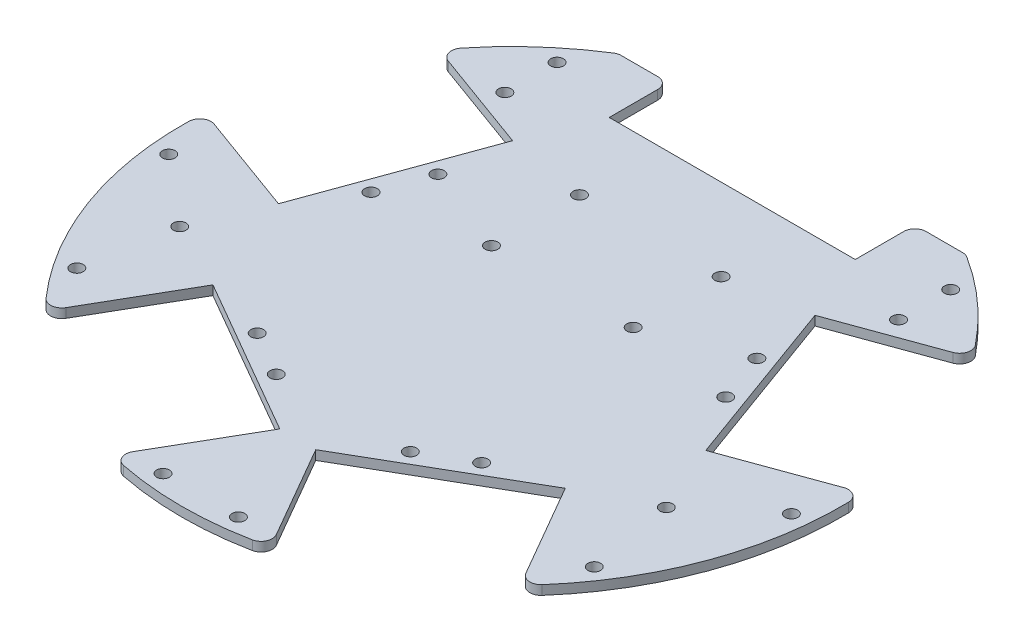
SolidWorks part; units mm, degrees
ref_plane "Front Plane" through (0, 0, 0) normal (0, 0, 1) x (1, 0, 0)
ref_plane "Top Plane" through (0, 0, 0) normal (0, 1, 0) x (1, 0, 0)
ref_plane "Right Plane" through (0, 0, 0) normal (1, 0, 0) x (0, 0, -1)
sketch "Sketch1" plane through (0, 0, 0) normal (0, 1, 0) x (1, 0, 0)
  line L0 (-33, 83.1941) -> (-33, 59.1941)
  line L1 (-33, 59.1941) -> (33, 59.1941)
  line L2 (33, 59.1941) -> (33, 83.1941)
  line L3 (-40.561, 40.8353) -> (-72.5105, 52.464)
  line L4 (-40.561, 40.8353) -> (-57.32, -5.2096)
  line L5 (-57.32, -5.2096) -> (-89.2695, 6.4191)
  line L6 (-64.2583, -62.2986) -> (-47.2583, -32.8538)
  line L7 (-47.2583, -32.8538) -> (-4.8231, -57.3538)
  line L8 (-4.8231, -57.3538) -> (-21.8231, -86.7986)
  line L9 (0, 0) -> (-48.9405, 17.8129) construction
  line L10 (0, 0) -> (-26.0407, -45.1038) construction
  line L11 (0, 0) -> (0, 40.1014) construction
  line L12 (0, 0) -> (61.2605, 0) construction
  line L13 (4.8231, -57.3538) -> (21.8231, -86.7986)
  line L14 (47.2583, -32.8538) -> (4.8231, -57.3538)
  line L15 (64.2583, -62.2986) -> (47.2583, -32.8538)
  line L16 (57.32, -5.2096) -> (89.2695, 6.4191)
  line L17 (40.561, 40.8353) -> (72.5105, 52.464)
  line L18 (40.561, 40.8353) -> (57.32, -5.2096)
  line L19 (-30.1029, -38.1397) -> (-17.9785, -45.1397) construction
  line L20 (-24.0407, -41.6397) -> (-26.0407, -45.1038) construction
  line L21 (-47.5758, 9.8669) -> (-42.7876, 23.0226) construction
  line L22 (-45.1817, 16.4448) -> (-48.9405, 17.8129) construction
  line L23 (65.2686, -23.7558) -> (71.3566, -7.0293) construction
  line L25 (0, 0) -> (84.1025, -30.6108) construction
  arc A0 (-89.2695, 6.4191) -> (-64.2583, -62.2986) centre (0, 0) ccw
  arc A1 (-33, 83.1941) -> (-72.5105, 52.464) centre (0, 0) ccw
  arc A2 (72.5105, 52.464) -> (33, 83.1941) centre (0, 0) ccw
  arc A3 (64.2583, -62.2986) -> (89.2695, 6.4191) centre (0, 0) ccw
  arc A4 (-21.8231, -86.7986) -> (21.8231, -86.7986) centre (0, 0) ccw
  circle A5 centre (65.2686, -23.7558) radius 17.8 construction
  circle A6 centre (65.2686, -23.7558) radius 20.1464 construction
  circle A7 centre (65.2686, -23.7558) radius 19.25 construction
  circle A8 centre (68.3126, -15.3926) radius 0.5
  circle A9 centre (62.2246, -32.1191) radius 0.5
  circle A10 centre (-68.3126, -15.3926) radius 0.5
  circle A11 centre (-62.2246, -32.1191) radius 0.5
  point P1 (-42.7876, 23.0226)
  point P6 (-47.5758, 9.8669)
  point P9 (-26.0407, -45.1038)
  point P12 (-48.9405, 17.8129)
  point P32 (0, 59.1941)
  point P33 (-30.1029, -38.1397)
  point P34 (-17.9785, -45.1397)
  point P44 (17.9785, -45.1397)
  point P45 (30.1029, -38.1397)
  point P46 (47.5758, 9.8669)
  point P47 (42.7876, 23.0226)
  point P49 (68.3126, -15.3926)
  point P51 (62.2246, -32.1191)
  point P52 (-62.2246, -32.1191)
  point P53 (-68.3126, -15.3926)
  point P65 (-65.2686, -23.7558)
  point P68 (65.2686, -23.7558)
  dimension "D1" = 179
  dimension "D14" = 35.6
  dimension "D15" = 40.2927
  dimension "D16" = 0
  dimension "D17" = 38.5
  dimension "D18" = 1
  dimension "D20" = 24
  dimension "D2" = 70
  dimension "D3" = 30
  dimension "D4" = 34
  dimension "D5" = 34
  dimension "D6" = 49
  dimension "D7" = 49
  dimension "D8" = 9.6461
  dimension "D9" = 14
  dimension "D10" = 4
  dimension "D11" = 14
  dimension "D12" = 4
  dimension "D13" = 66
  dimension "D19" = 8.9
extrude "cutoff profile" add sketch "Sketch1" along normal blind 2.5 contours L8 A4 L13 L14 L15 A3 L16 L18 L17 A2 L2 L1 L0 A1 L3 L4 L5 A0 L6 L7 A11 A10 A9 A8
sketch "Sketch3" plane through (0, 2.5, 0) normal (0, 1, 0) x (1, 0, 0)
  line L0 (-48.9405, 17.8129) -> (-45.1817, 16.4448) construction
  line L2 (-42.7876, 23.0226) -> (-47.5758, 9.8669) construction
  line L3 (-26.0407, -45.1038) -> (-24.0407, -41.6397) construction
  line L5 (-30.1029, -38.1397) -> (-17.9785, -45.1397) construction
  line L6 (0, 0) -> (0, 78.2357) construction
  line L7 (0, 0) -> (75.9259, 0) construction
  line L8 (0, 0) -> (-48.9405, 17.8129) construction
  line L9 (0, 0) -> (-26.0407, -45.1038) construction
  line L10 (-4.8231, -57.3538) -> (0, -49) construction
  line L14 (4.8231, -57.3538) -> (0, -49) construction
  line L19 (68.3126, -15.3926) -> (62.2246, -32.1191)
  line L20 (-40.561, 40.8353) -> (-57.32, -5.2096) construction
  line L21 (-47.2583, -32.8538) -> (-4.8231, -57.3538) construction
  line L22 (-52.8, 51) -> (-52.8, 65) construction
  point P17 (-24.0407, -41.6397)
  point P18 (-17.9785, -45.1397)
  point P19 (-45.1817, 16.4448)
  point P20 (-47.5758, 9.8669)
  point P21 (-30.1029, -38.1397)
  point P22 (-42.7876, 23.0226)
  point P23 (17.9785, -45.1397)
  point P24 (30.1029, -38.1397)
  point P25 (47.5758, 9.8669)
  point P26 (42.7876, 23.0226)
  point P27 (68.3126, -15.3926)
  point P30 (62.2246, -32.1191)
  point P33 (-62.2246, -32.1191)
  point P36 (-68.3126, -15.3926)
  point P72 (65.2686, -23.7558)
  point P75 (-65.2686, -23.7558)
  point P95 (-52.8, 51)
  point P98 (52.8, 51)
  point P105 (-52.8, 65)
  point P107 (52.8, 65)
  dimension "D6" = 52.8
  dimension "D1" = 14
  dimension "D2" = 4
  dimension "D3" = 4
  dimension "D4" = 14
  dimension "D7" = 51
  dimension "D8" = 14
hole_wizard "flanged holes" positions "Sketch3" profile "Sketch4" hole size "M3" standard "ANSI Metric"
sketch "Sketch4" plane through (52.8, 2.5, -65) normal (1, 0, 0) x (0, 0, 1)
  line L0 (0, 0) -> (0, 2.5)
  line L1 (0, 2.5) -> (1.7, 2.5)
  line L2 (1.7, 2.5) -> (1.7, 0)
  line L5 (1.7, 0) -> (0, 0)
  line L11 (0, -6.35) -> (0, 107.95) construction
  dimension "Thru Hole Dia." = 3.4
  dimension "Thru Hole Depth" = 2.5
sketch "Sketch5" plane through (0, 2.5, 0) normal (0, 1, 0) x (1, 0, 0)
  line L0 (-4.8231, -57.3538) -> (-21.8231, -86.7986) construction
  line L1 (4.8231, -57.3538) -> (21.8231, -86.7986) construction
  line L2 (0, -71.1138) -> (0, -88.5)
  line L3 (4.8231, -57.3538) -> (2.4115, -61.7338)
  line L4 (-21.303, -85.8978) -> (-21.8231, -86.7986)
  line L5 (21.303, -85.8978) -> (21.8231, -86.7986)
  line L6 (-4.8231, -57.3538) -> (-21.8231, -86.7986) construction
  line L8 (64.2583, -62.2986) -> (63.7382, -61.3978)
  line L9 (-63.7382, -61.3978) -> (-64.2583, -62.2986)
  line L10 (-64.2583, -62.2986) -> (-47.2583, -32.8538) construction
  line L11 (64.2583, -62.2986) -> (47.2583, -32.8538) construction
  arc A0 (-21.8231, -86.7986) -> (21.8231, -86.7986) centre (0, 0) ccw
  arc A2 (-21.303, -85.8978) -> (21.303, -85.8978) centre (0, 0) ccw
  circle A3 centre (0, -66.1138) radius 5
  arc A4 (-64.2583, -62.2986) -> (64.2583, -62.2986) centre (0, 0) cw
  arc A5 (-21.8231, -86.7986) -> (21.8231, -86.7986) centre (0, 0) ccw construction
  arc A6 (-63.7382, -61.3978) -> (63.7382, -61.3978) centre (0, 0) cw
  point P18 (0, -71.1138)
  dimension "D1" = 10
  dimension "D4" = 1
  dimension "D5" = 88.5
  dimension "D2" = 88.5
  dimension "D3" = 5
extrude "excess cut" cut sketch "Sketch5" against normal blind 10
sketch "Sketch7" plane through (0, 2.5, 0) normal (0, 1, 0) x (1, 0, 0)
  line L0 (-33, 82.1173) -> (-33, 65.6173) construction
  line L2 (-33, 65.6173) -> (0, 65.6173) construction
  line L3 (0, 65.6173) -> (0, 37.2173) construction
  line L4 (0, 37.2173) -> (-19, 37.2173) construction
  line L5 (-19, 37.2173) -> (-19, 13.6173) construction
  point P12 (-19, 13.6173)
  point P13 (-19, 37.2173)
  point P14 (19, 13.6173)
  point P15 (19, 37.2173)
  dimension "D1" = 16.5
  dimension "D2" = 28.4
  dimension "D3" = 19
  dimension "D4" = 23.6
hole_wizard "M3 Clearance Hole1" positions "Sketch7" profile "Sketch8" hole size "M3" standard "ANSI Metric" end condition through all
sketch "Sketch8" plane through (19, 2.5, -37.2173) normal (1, 0, 0) x (0, 0, 1)
  line L0 (0, 0) -> (0, 2.5)
  line L1 (0, 2.5) -> (1.7, 2.5)
  line L2 (1.7, 2.5) -> (1.7, 0)
  line L5 (1.7, 0) -> (0, 0)
  line L11 (0, -6.35) -> (0, 107.95) construction
  dimension "Thru Hole Dia." = 3.4
  dimension "Thru Hole Depth" = 2.5
fillet "Fillet1" radius 3 10 edges at (-63.7382, 1.25, 61.3978) (21.303, 1.25, 85.8978) (-21.303, 1.25, 85.8978) (63.7382, 1.25, 61.3978) (88.2921, 1.25, -6.0633) (71.5331, 1.25, -52.1083) (33, 1.25, -82.1173) (-88.2921, 1.25, -6.0633) (-71.5331, 1.25, -52.1083) (-33, 1.25, -82.1173)
sketch "Sketch9" plane through (0, 2.5, 0) normal (0, 1, 0) x (1, 0, 0)
  line L0 (-36, 80.5516) -> (-36, 75.2016) construction
  line L1 (-46.658, 75.2016) -> (56.8451, 75.2016)
  line L2 (56.8451, 75.2016) -> (56.8451, 82.96)
  line L3 (56.8451, 82.96) -> (-46.658, 82.96)
  line L4 (-46.658, 82.96) -> (-46.658, 75.2016)
  arc A0 (-33, 77.5516) -> (-37.2632, 80.2727) centre (-36, 77.5516) ccw construction
  arc A1 (-37.2632, 80.2727) -> (-69.0082, 55.4087) centre (0, 0) ccw construction
  arc M43 (69.0082, 55.4087) -> (37.2632, 80.2727) centre (0, 0) ccw
  arc M44 (37.2632, 80.2727) -> (33, 77.5516) centre (36, 77.5516) ccw
  line M45 (33, 77.5516) -> (33, 59.1941)
  line M47 (-33, 59.1941) -> (-33, 77.5516)
  arc M48 (-33, 77.5516) -> (-37.2632, 80.2727) centre (-36, 77.5516) ccw
  arc M49 (-37.2632, 80.2727) -> (-69.0082, 55.4087) centre (0, 0) ccw
  dimension "D1" = 5.35
extrude "Cut-Extrude2" cut sketch "Sketch9" against normal up to next (2.5 mm away) contours L3 L4 L1 L2 M49 M48 M47 M45 M44 M43 | L0 L1 M48 M49 | L0 L1 M48 M47 | L1 M45 M43 M44
fillet "Fillet2" radius 3 4 edges at (-46.658, 1.25, -75.2016) (46.658, 1.25, -75.2016) (33, 1.25, -75.2016) (-33, 1.25, -75.2016)
sketch "Sketch10" plane through (0, 2.5, 0) normal (0, 1, 0) x (1, 0, 0)
  line L0 (-20.5219, -84.545) -> (-17.3853, -79.1123) construction
  line L1 (-86.8241, 5.529) -> (-80.9293, 3.3835) construction
  line L2 (86.8241, 5.529) -> (80.9293, 3.3835) construction
  line L3 (-65.2686, -23.7558) -> (-110.5174, -40.2251) construction
  line L4 (-65.2686, -23.7558) -> (-102.3819, 7.3859) construction
  line L5 (-65.2686, -23.7558) -> (-73.6815, -71.4677) construction
  line L6 (-68.658, -42.9777) -> (-70.1527, -51.4548) construction
  line L7 (-86.8146, -5.6766) -> (-80.2206, -11.2096) construction
  line L8 (0, 0) -> (0, -87) construction
  line L9 (0, -59) -> (-15.6883, -96.8749) construction
  line L10 (0, -59) -> (15.6883, -96.8749) construction
  line L11 (-11.2931, -86.2639) -> (-8.9091, -80.5086) construction
  line L12 (11.2931, -86.2639) -> (8.9091, -80.5086) construction
  line L13 (-62.9441, -60.0586) -> (-59.8206, -54.6123) construction
  line L14 (20.5219, -84.545) -> (17.3853, -79.1123) construction
  line L15 (62.9441, -60.0586) -> (59.8206, -54.6123) construction
  arc A0 (-86.8241, 5.529) -> (-62.9441, -60.0586) centre (0, 0) ccw construction
  arc A1 (-80.9293, 3.3835) -> (-59.8206, -54.6123) centre (0, 0) ccw construction
  circle A2 centre (-69.4053, -47.2163) radius 1.7 construction
  arc A3 (59.8206, -54.6123) -> (80.9293, 3.3835) centre (0, 0) ccw construction
  arc A4 (62.9441, -60.0586) -> (86.8241, 5.529) centre (0, 0) ccw construction
  circle A5 centre (-83.5176, -8.4431) radius 1.7 construction
  arc A6 (-17.3853, -79.1123) -> (17.3853, -79.1123) centre (0, 0) ccw construction
  arc A7 (-20.5219, -84.545) -> (20.5219, -84.545) centre (0, 0) ccw construction
  circle A8 centre (69.4053, -47.2163) radius 1.7 construction
  circle A9 centre (83.5176, -8.4431) radius 1.7 construction
  circle A10 centre (-10.1011, -83.3862) radius 1.7 construction
  circle A11 centre (10.1011, -83.3862) radius 1.7 construction
  point P39 (-69.4053, -47.2163)
  point P40 (-83.5176, -8.4431)
  point P41 (10.1011, -83.3862)
  point P42 (-10.1011, -83.3862)
  point P43 (69.4053, -47.2163)
  point P44 (83.5176, -8.4431)
  dimension "D2" = 3.4
  dimension "D4" = 3.4
  dimension "D1" = 60
  dimension "D3" = 22.5
  dimension "D5" = 168
  dimension "D6" = 8.6079
hole_wizard "M3 Clearance Hole2" positions "Sketch10" profile "Sketch11" hole size "M3" standard "ANSI Metric" end condition through all
sketch "Sketch11" plane through (83.5176, 2.5, 8.4431) normal (1, 0, 0) x (0, 0, 1)
  line L0 (0, 0) -> (0, 2.5)
  line L1 (0, 2.5) -> (1.7, 2.5)
  line L2 (1.7, 2.5) -> (1.7, 0)
  line L5 (1.7, 0) -> (0, 0)
  line L11 (0, -6.35) -> (0, 107.95) construction
  dimension "Thru Hole Dia." = 3.4
  dimension "Thru Hole Depth" = 2.5
sketch "Sketch13" plane through (0, 0, 0) normal (0, -1, 0) x (1, 0, 0)
  line L0 (-36, -75.2016) -> (-45.795, -75.2016) construction
  line L1 (-88.5, -75.2016) -> (88.4793, -75.2016)
  line L2 (-88.5, -75.2016) -> (-88.5, 88.5)
  line L3 (-88.5, 88.5) -> (88.4793, 88.5)
  line L4 (88.4793, -75.2016) -> (88.4793, 88.5)
  arc A0 (17.2473, 86.8031) -> (-17.2473, 86.8031) centre (0, 0) ccw construction
  arc A1 (-66.55, 58.3382) -> (-88.4793, -1.9121) centre (0, 0) ccw construction
  point P0 (0, 0)
sketch "Sketch14" plane through (0, 0, 0) normal (0, -1, 0) x (1, 0, 0)
  line L0 (0, 0) -> (-26.0407, 45.1038)
  line L1 (-47.2583, 32.8538) -> (-4.8231, 57.3538) construction
  line L2 (0, 0) -> (26.0407, 45.1038)
  line L3 (47.2583, 32.8538) -> (4.8231, 57.3538) construction
  line L4 (0, 0) -> (48.9405, -17.8129)
  line L5 (40.561, -40.8353) -> (57.32, 5.2096) construction
  line L6 (0, 0) -> (-48.9405, -17.8129)
  line L7 (-40.561, -40.8353) -> (-57.32, 5.2096) construction
